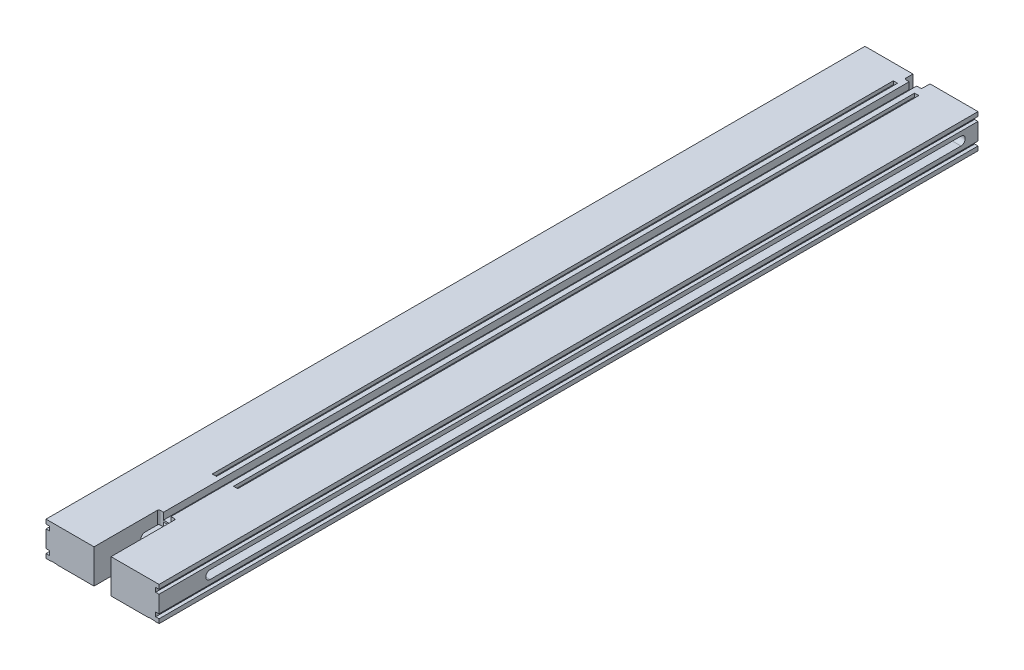
SolidWorks part; units mm, degrees
ref_plane "Front Plane" through (0, 0, 0) normal (0, 0, 1) x (1, 0, 0)
ref_plane "Top Plane" through (0, 0, 0) normal (0, 1, 0) x (1, 0, 0)
ref_plane "Right Plane" through (0, 0, 0) normal (1, 0, 0) x (0, 0, -1)
sketch "Sketch1" plane through (0, 0, 0) normal (0, 0, 1) x (1, 0, 0)
  line L32 (83.3867, 0) -> (80.2117, 0)
  line L33 (80.2117, 0) -> (80.2117, 0.254)
  line L34 (80.2117, 0.254) -> (75.3857, 0.254)
  line L35 (75.3857, 0.254) -> (75.3857, 0)
  line L36 (75.3857, 0) -> (7.0597, 0)
  line L37 (7.0597, 0) -> (7.0597, 0.254)
  line L38 (7.0597, 0.254) -> (2.2337, 0.254)
  line L39 (2.2337, 0.254) -> (2.2337, 0)
  line L40 (2.2337, 0) -> (-0.9413, 0)
  line L41 (83.3867, 0) -> (83.3867, 25.4)
  line L42 (83.3867, 25.4) -> (-0.9413, 25.4)
  line L43 (-0.9413, 25.4) -> (-0.9413, 0)
  dimension "D1" = 84.328
  dimension "D2" = 3.175
  dimension "D3" = 3.175
  dimension "D4" = 4.826
  dimension "D5" = 4.826
  dimension "D6" = 68.326
  dimension "D7" = 0.254
  dimension "D8" = 0.254
  dimension "D9" = 25.4
  dimension "D10" = 25.4
extrude "Boss-Extrude1" add sketch "Sketch1" along normal blind 584.2 and the other way blind 1.27
sketch "Sketch2" plane through (0, 0, 0) normal (0, -1, 0) x (1, 0, 0)
  line L0 (41.2227, -1.27) -> (41.2227, 584.2) construction
  line L1 (7.0597, -1.27) -> (75.3857, -1.27) construction
  line L2 (7.0597, 584.2) -> (75.3857, 584.2) construction
  line L3 (41.2227, 27.305) -> (41.2227, 555.625) construction
  line L4 (34.8727, 27.305) -> (34.8727, 555.625)
  line L5 (47.5727, 27.305) -> (47.5727, 555.625)
  arc A0 (34.8727, 27.305) -> (47.5727, 27.305) centre (41.2227, 27.305) ccw
  arc A1 (47.5727, 555.625) -> (34.8727, 555.625) centre (41.2227, 555.625) ccw
  point P8 (41.2227, 291.465)
  dimension "D1" = 12.7
  dimension "D2" = 28.575
  dimension "D3" = 28.575
extrude "Cut-Extrude1" cut sketch "Sketch2" against normal blind 19.05
sketch "Sketch3" plane through (83.3867, 0, 0) normal (1, 0, 0) x (0, 0, -1)
  line L0 (1.27, 22.225) -> (-584.2, 22.225)
  line L1 (1.27, 0) -> (1.27, 25.4) construction
  line L2 (-584.2, 0) -> (-584.2, 25.4) construction
  line L3 (-584.2, 22.225) -> (-584.2, 19.05)
  line L4 (-584.2, 19.05) -> (1.27, 19.05)
  line L5 (1.27, 19.05) -> (1.27, 22.225)
  line L7 (1.27, 25.4) -> (-584.2, 25.4) construction
  dimension "D1" = 3.175
  dimension "D2" = 3.175
extrude "Cut-Extrude2" cut sketch "Sketch3" against normal blind 2.54
sketch "Sketch4" plane through (83.3867, 0, 0) normal (1, 0, 0) x (0, 0, -1)
  line L0 (1.27, 6.35) -> (-584.2, 6.35)
  line L1 (1.27, 0) -> (1.27, 19.05) construction
  line L2 (-584.2, 0) -> (-584.2, 19.05) construction
  line L3 (-584.2, 6.35) -> (-584.2, 3.175)
  line L4 (-584.2, 3.175) -> (1.27, 3.175)
  line L5 (1.27, 3.175) -> (1.27, 6.35)
  line L6 (1.27, 0) -> (-584.2, 0) construction
  dimension "D1" = 585.47
  dimension "D2" = 3.175
  dimension "D3" = 3.175
extrude "Cut-Extrude3" cut sketch "Sketch4" against normal blind 2.54
sketch "Sketch5" plane through (-0.9413, 0, 0) normal (-1, 0, 0) x (0, 0, 1)
  line L0 (-1.27, 3.175) -> (-1.27, 6.35)
  line L1 (-1.27, 25.4) -> (-1.27, 0) construction
  line L2 (-1.27, 6.35) -> (584.2, 6.35)
  line L3 (584.2, 25.4) -> (584.2, 0) construction
  line L4 (584.2, 6.35) -> (584.2, 3.175)
  line L5 (584.2, 3.175) -> (-1.27, 3.175)
  line L6 (-1.27, 0) -> (584.2, 0) construction
  dimension "D1" = 3.175
  dimension "D2" = 3.175
  dimension "D3" = 3.175
extrude "Cut-Extrude4" cut sketch "Sketch5" against normal blind 2.54
sketch "Sketch6" plane through (-0.9413, 0, 0) normal (-1, 0, 0) x (0, 0, 1)
  line L0 (-1.27, 19.05) -> (-1.27, 22.225)
  line L1 (-1.27, 25.4) -> (-1.27, 6.35) construction
  line L2 (-1.27, 22.225) -> (584.2, 22.225)
  line L3 (584.2, 25.4) -> (584.2, 6.35) construction
  line L4 (584.2, 22.225) -> (584.2, 19.05)
  line L5 (584.2, 19.05) -> (-1.27, 19.05)
  line L6 (-1.27, 25.4) -> (584.2, 25.4) construction
  dimension "D1" = 3.175
  dimension "D2" = 3.175
  dimension "D3" = 3.175
extrude "Cut-Extrude5" cut sketch "Sketch6" against normal blind 2.54
sketch "Sketch7" plane through (83.3867, 0, 0) normal (1, 0, 0) x (0, 0, -1)
  line L0 (1.27, 12.7) -> (-462.032, 12.7) construction
  line L1 (1.27, 6.35) -> (1.27, 19.05) construction
  line L2 (-11.43, 12.7) -> (-571.5, 12.7) construction
  line L3 (-11.43, 9.5123) -> (-571.5, 9.5123)
  line L4 (-11.43, 15.8877) -> (-571.5, 15.8877)
  line L5 (-584.2, 6.35) -> (-584.2, 19.05) construction
  arc A0 (-11.43, 9.5123) -> (-11.43, 15.8877) centre (-11.43, 12.7) ccw
  arc A1 (-571.5, 15.8877) -> (-571.5, 9.5123) centre (-571.5, 12.7) ccw
  point P6 (-291.465, 12.7)
  dimension "D1" = 12.7
  dimension "D2" = 12.7
  dimension "D3" = 6.3754
extrude "Cut-Extrude6" cut sketch "Sketch7" against normal through all
sketch "Sketch8" plane through (0, 0, -1.27) normal (0, 0, -1) x (-1, 0, 0)
  line L0 (-41.2227, 0) -> (-41.2227, 28.5873) construction
  line L1 (-7.0597, 0) -> (-75.3857, 0) construction
sketch "Sketch9" plane through (0, 0, 0) normal (0, -1, 0) x (1, 0, 0)
  line L0 (47.5727, -1.27) -> (34.8727, -1.27)
  line L1 (7.0597, -1.27) -> (75.3857, -1.27) construction
  line L2 (41.2227, 5.08) -> (34.8727, 5.08)
  line L3 (34.8727, 5.08) -> (34.8727, -1.27)
  line L4 (41.2227, 5.08) -> (47.5727, 5.08)
  line L5 (47.5727, 5.08) -> (47.5727, -1.27)
  line L6 (83.3867, -1.27) -> (83.3867, 584.2) construction
  dimension "D1" = 6.35
  dimension "D2" = 6.35
  dimension "D3" = 6.35
  dimension "D4" = 35.814
sketch "Sketch10" plane through (0, 25.4, 0) normal (0, 1, 0) x (1, 0, 0)
  line L0 (41.2227, -584.2) -> (41.2227, -543.4853) construction
  line L1 (83.3867, -584.2) -> (-0.9413, -584.2) construction
  line L2 (41.2227, -584.2) -> (47.5727, -584.2)
  line L3 (47.5727, -584.2) -> (47.5727, -561.34)
  line L4 (47.5727, -561.34) -> (34.8727, -561.34)
  line L5 (34.8727, -561.34) -> (34.8727, -584.2)
  line L6 (34.8727, -584.2) -> (41.2227, -584.2)
  dimension "D1" = 6.35
  dimension "D2" = 6.35
  dimension "D3" = 22.86
extrude "Cut-Extrude8" cut sketch "Sketch10" against normal through all contours L6 L2 L3 L4 L5
fillet "Fillet4" radius 1.016 2 edges at (47.5727, 20.6438, 561.34) (34.8727, 20.6438, 561.34)
extrude "Cut-Extrude9" cut sketch "Sketch9" against normal through all contours L0 L3 L2 L4 L5
fillet "Fillet5" radius 1.016 2 edges at (34.8727, 12.7, 5.08) (47.5727, 12.7, 5.08)
sketch "Sketch11" plane through (0, 0, 0) normal (0, -1, 0) x (1, 0, 0)
  circle A0 centre (19.5759, 541.4535) radius 7.7884
sketch "Sketch12" plane through (0, 25.4, 0) normal (0, 1, 0) x (1, 0, 0)
  line L1 (35.0934, -10.4408) -> (35.0934, -518.4408)
  line L3 (47.7934, -13.5087) -> (47.7934, -10.4408)
  line L5 (35.0934, -13.5087) -> (35.0934, -20.3467)
  line L7 (47.7934, -13.5087) -> (47.7934, -20.3467)
  line L10 (47.7934, -10.4408) -> (50.9684, -10.4408)
  line L11 (50.9684, -10.4408) -> (50.9684, -518.4408)
  line L12 (50.9684, -518.4408) -> (47.7934, -518.4408)
  line L13 (47.7934, -518.4408) -> (47.7934, -10.4408)
  line L14 (35.0934, -13.5087) -> (35.0934, -10.4408)
  line L15 (35.0934, -10.4408) -> (31.9184, -10.4408)
  line L16 (31.9184, -10.4408) -> (31.9184, -518.4408)
  line L17 (35.0934, -518.4408) -> (31.9184, -518.4408)
  point P4 (41.2227, -16.9277)
  dimension "D1" = 12.7
  dimension "D2" = 3.175
  dimension "D3" = 3.175
  dimension "D4" = 508
  dimension "D5" = 508
  dimension "D6" = 3.175
  dimension "D7" = 3.175
extrude "Cut-Extrude10" cut sketch "Sketch12" against normal blind 2.54 contours L17 L1 L15 L16 | L13 L12 L11 L10 L3 L7
sketch "Sketch13" plane through (0, 25.4, 0) normal (0, 1, 0) x (1, 0, 0)
  line L0 (41.2227, -5.08) -> (41.2227, -63.0753) construction
  line L1 (46.5567, -5.08) -> (35.8887, -5.08) construction
  line L2 (35.0934, -10.4408) -> (31.9184, -10.4408) construction
  line L3 (38.4287, 14.9592) -> (44.0167, 14.9592)
  line L4 (38.4287, 14.9592) -> (38.4287, -620.0408)
  line L5 (38.4287, -620.0408) -> (44.0167, -620.0408)
  line L6 (44.0167, 14.9592) -> (44.0167, -620.0408)
  line L7 (38.4287, 14.9592) -> (44.0167, -620.0408) construction
  line L8 (38.4287, -620.0408) -> (44.0167, 14.9592) construction
  line L9 (35.0934, -518.4408) -> (31.9184, -518.4408) construction
  point P4 (41.2227, -302.5408)
  dimension "D1" = 25.4
  dimension "D2" = 101.6
  dimension "D3" = 5.588
sketch "Sketch14" plane through (0, 0, 584.2) normal (0, 0, 1) x (1, 0, 0)
sketch "Sketch15" plane through (0, 0, 584.2) normal (0, 0, 1) x (1, 0, 0)
  line L0 (-0.9413, 25.4) -> (34.8727, 25.4)
  line L1 (34.8727, 25.4) -> (34.8727, 0)
  line L2 (34.8727, 0) -> (7.0597, 0)
  line L3 (7.0597, 0) -> (7.0597, 0.254)
  line L4 (7.0597, 0.254) -> (2.2337, 0.254)
  line L5 (2.2337, 0.254) -> (2.2337, 0)
  line L6 (-0.9413, 0) -> (2.2337, 0) construction
  line L7 (2.2337, 0) -> (-0.9413, 0)
  line L8 (-0.9413, 0) -> (-0.9413, 3.175)
  line L9 (-0.9413, 3.175) -> (1.5987, 3.175)
  line L10 (1.5987, 3.175) -> (1.5987, 6.35)
  line L11 (1.5987, 6.35) -> (-0.9413, 6.35)
  line L12 (-0.9413, 6.35) -> (-0.9413, 19.05)
  line L13 (-0.9413, 19.05) -> (1.5987, 19.05)
  line L14 (1.5987, 19.05) -> (1.5987, 22.225)
  line L15 (1.5987, 22.225) -> (-0.9413, 22.225)
  line L16 (-0.9413, 22.225) -> (-0.9413, 25.4)
  line L17 (47.5727, 0) -> (47.5727, 25.4)
  line L18 (47.5727, 25.4) -> (83.3867, 25.4)
  line L19 (83.3867, 25.4) -> (83.3867, 22.225)
  line L20 (83.3867, 22.225) -> (80.8467, 22.225)
  line L21 (80.8467, 22.225) -> (80.8467, 19.05)
  line L22 (80.8467, 19.05) -> (83.3867, 19.05)
  line L23 (83.3867, 19.05) -> (83.3867, 6.35)
  line L24 (83.3867, 6.35) -> (80.8467, 6.35)
  line L25 (80.8467, 6.35) -> (80.8467, 3.175)
  line L26 (80.8467, 3.175) -> (83.3867, 3.175)
  line L27 (83.3867, 3.175) -> (83.3867, 0)
  line L28 (83.3867, 0) -> (80.2117, 0)
  line L29 (80.2117, 0) -> (80.2117, 0.254)
  line L30 (80.2117, 0.254) -> (75.3857, 0.254)
  line L31 (75.3857, 0.254) -> (75.3857, 0)
  line L32 (75.3857, 0) -> (47.5727, 0)
extrude "Boss-Extrude3" add sketch "Sketch15" along normal blind 25.4
extrude "Cut-Extrude11" cut sketch "Sketch13" against normal blind 5.08
